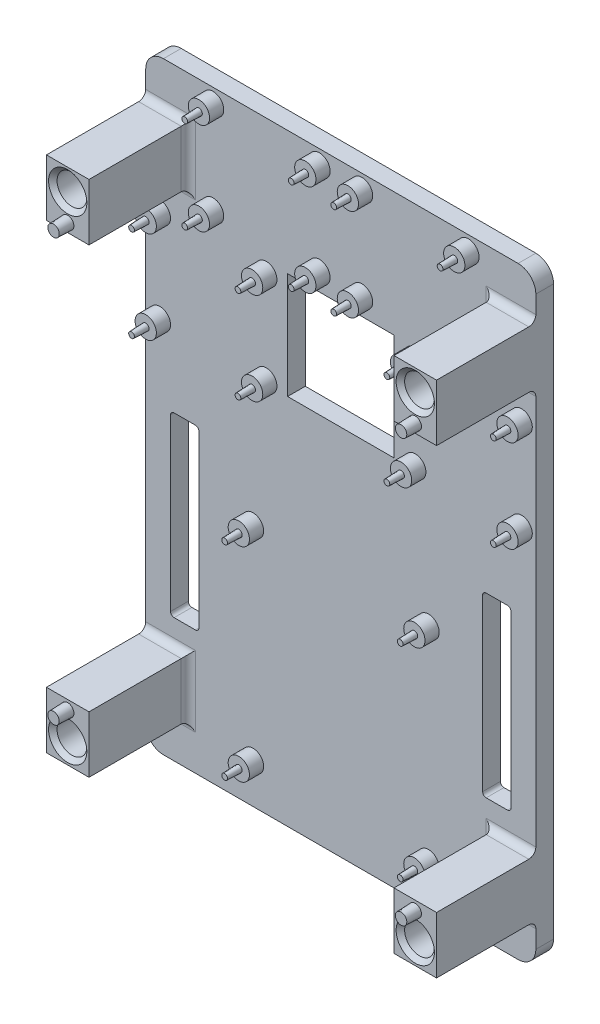
SolidWorks part; units mm, degrees
ref_plane "Ebene vorne" through (0, 0, 0) normal (0, 0, 1) x (1, 0, 0)
ref_plane "Ebene oben" through (0, 0, 0) normal (0, 1, 0) x (1, 0, 0)
ref_plane "Ebene rechts" through (0, 0, 0) normal (1, 0, 0) x (0, 0, -1)
sketch "Skizze1" plane through (0, 0, 0) normal (0, 0, 1) x (1, 0, 0)
  line L1 (-55, -85) -> (55, -85)
  line L2 (-55, -85) -> (-55, 85)
  line L3 (-55, 85) -> (55, 85)
  line L4 (55, -85) -> (55, 85)
  line L5 (-55, -85) -> (55, 85) construction
  line L6 (-55, 85) -> (55, -85) construction
  point P0 (0, 0)
  dimension "D1" = 110
  dimension "D2" = 170
extrude "Aufsatz-Linear austragen1" add sketch "Skizze1" along normal blind 5
fillet "Verrundung1" radius 5 4 edges at (-55, -85, 2.5) (55, -85, 2.5) (55, 85, 2.5) (-55, 85, 2.5)
sketch "Skizze7" plane through (0, 0, 5) normal (0, 0, 1) x (1, 0, 0)
  line L0 (-55, 80) -> (-55, -80) construction
  line L1 (-55, 73) -> (-43, 73)
  line L2 (-55, 73) -> (-55, 57)
  line L3 (-55, 57) -> (-43, 57)
  line L4 (-43, 73) -> (-43, 57)
  line L5 (50, 85) -> (-50, 85) construction
  line L18 (0, 85) -> (0, -85) construction
  line L19 (-50, -85) -> (50, -85) construction
  line L20 (-55, 0) -> (55, 0) construction
  line L21 (55, -80) -> (55, 80) construction
  line L22 (43, 73) -> (43, 57)
  line L23 (55, 57) -> (43, 57)
  line L24 (55, 73) -> (55, 57)
  line L25 (55, 73) -> (43, 73)
  line L26 (55, -73) -> (43, -73)
  line L27 (55, -73) -> (55, -57)
  line L28 (55, -57) -> (43, -57)
  line L29 (43, -73) -> (43, -57)
  line L30 (-43, -73) -> (-43, -57)
  line L31 (-55, -57) -> (-43, -57)
  line L32 (-55, -73) -> (-55, -57)
  line L33 (-55, -73) -> (-43, -73)
  dimension "D1" = 12
  dimension "D2" = 16
  dimension "D3" = 12
extrude "Aufsatz-Linear austragen3" add sketch "Skizze7" along normal blind 28
fillet "Verrundung2" radius 2 12 edges at (-49, 73, 5) (-49, 57, 5) (-43, 65, 5) (-49, -57, 5) (-43, -65, 5) (-49, -73, 5) (49, -73, 5) (43, -65, 5) (49, -57, 5) (49, 57, 5) (43, 65, 5) (49, 73, 5)
sketch "Skizze8" plane through (0, 0, 33) normal (0, 0, 1) x (1, 0, 0)
  line L0 (-43, 73) -> (-55, 73) construction
  line L1 (-55, 73) -> (-55, 57) construction
  line L5 (-55, 31.954) -> (-55, -16.1316) construction
  line L8 (-55, 55) -> (-55, -55) construction
  circle A1 centre (-49, 67) radius 4.2
  point P12 (0, 0)
  dimension "D1" = 8.4
  dimension "D2" = 6
  dimension "D3" = 6
extrude "Schnitt-Linear austragen3" cut sketch "Skizze8" against normal through all
pattern_linear "Lineares Muster1" count 2 spacing 134 along (0, -1, 0) count 2 spacing 98 along (1, 0, 0) of "Schnitt-Linear austragen3"
sketch "Skizze9" plane through (0, 0, 5) normal (0, 0, 1) x (1, 0, 0)
  line L0 (0, 85) -> (0, -85) construction
  line L1 (-28, -77) -> (28, -77) construction
  line L2 (-28, -77) -> (-28, 12) construction
  line L3 (-28, 12) -> (28, 12) construction
  line L4 (28, -77) -> (28, 12) construction
  line L5 (-28, -77) -> (28, 12) construction
  line L6 (-28, 12) -> (28, -77) construction
  line L11 (50, 85) -> (-50, 85) construction
  line L12 (-50, -85) -> (50, -85) construction
  line L13 (-55, 55) -> (-55, -55) construction
  line L14 (-51, 21) -> (-21, 21) construction
  line L15 (-51, 21) -> (-51, 47) construction
  line L16 (-51, 47) -> (-21, 47) construction
  line L17 (-21, 21) -> (-21, 47) construction
  line L18 (-51, 21) -> (-21, 47) construction
  line L19 (-51, 47) -> (-21, 21) construction
  line L21 (-36, 55) -> (-6, 55) construction
  line L22 (-36, 55) -> (-36, 81) construction
  line L23 (-36, 81) -> (-6, 81) construction
  line L24 (-6, 55) -> (-6, 81) construction
  line L25 (-36, 55) -> (-6, 81) construction
  line L26 (-36, 81) -> (-6, 55) construction
  line L27 (51, 47) -> (21, 47) construction
  line L28 (21, 21) -> (21, 47) construction
  line L29 (51, 21) -> (21, 21) construction
  line L30 (51, 21) -> (51, 47) construction
  line L31 (36, 81) -> (6, 81) construction
  line L32 (6, 55) -> (6, 81) construction
  line L33 (36, 55) -> (6, 55) construction
  line L34 (36, 55) -> (36, 81) construction
  circle A0 centre (24.75, -73.75) radius 3
  circle A1 centre (24.75, -16.25) radius 3
  circle A2 centre (-24.75, -16.25) radius 3
  circle A3 centre (-24.75, -73.75) radius 3
  circle A4 centre (-36, 81) radius 3
  circle A5 centre (-6, 81) radius 3
  circle A6 centre (-36, 55) radius 3
  circle A7 centre (-6, 55) radius 3
  circle A8 centre (6, 81) radius 3
  circle A9 centre (36, 81) radius 3
  circle A10 centre (36, 55) radius 3
  circle A11 centre (6, 55) radius 3
  circle A12 centre (21, 47) radius 3
  circle A13 centre (51, 47) radius 3
  circle A14 centre (51, 21) radius 3
  circle A15 centre (21, 21) radius 3
  circle A16 centre (-21, 47) radius 3
  circle A17 centre (-51, 47) radius 3
  circle A18 centre (-51, 21) radius 3
  circle A19 centre (-21, 21) radius 3
  point P0 (0, 0)
  point P5 (0, -32.5)
  point P21 (-36, 34)
  point P28 (-21, 68)
  dimension "D3" = 3.25
  dimension "D4" = 6
  dimension "D5" = 57.5
  dimension "D17" = 6
  dimension "D1" = 56
  dimension "D2" = 89
  dimension "D6" = 3.25
  dimension "D7" = 8
  dimension "D8" = 28
  dimension "D9" = 26
  dimension "D10" = 30
  dimension "D11" = 4
  dimension "D12" = 38
  dimension "D13" = 26
  dimension "D14" = 30
  dimension "D15" = 4
  dimension "D16" = 19
extrude "Aufsatz-Linear austragen4" add sketch "Skizze9" along normal blind 4
sketch "Skizze10" plane through (0, 0, 9) normal (0, 0, 1) x (1, 0, 0)
  line L0 (0, -85) -> (0, 85) construction
  line L1 (-50, -85) -> (50, -85) construction
  line L2 (50, 85) -> (-50, 85) construction
  circle A0 centre (24.75, -73.75) radius 0.95
  circle A1 centre (24.75, -16.25) radius 0.95
  circle A2 centre (-24.75, -16.25) radius 0.95
  circle A3 centre (-24.75, -73.75) radius 0.95
  circle A4 centre (-51, 47) radius 0.95
  circle A5 centre (-51, 21) radius 0.95
  circle A6 centre (-21, 21) radius 0.95
  circle A7 centre (-21, 47) radius 0.95
  circle A8 centre (-36, 55) radius 0.95
  circle A9 centre (-6, 55) radius 0.95
  circle A10 centre (6, 55) radius 0.95
  circle A11 centre (-36, 81) radius 0.95
  circle A12 centre (-6, 81) radius 0.95
  circle A13 centre (6, 81) radius 0.95
  circle A14 centre (36, 81) radius 0.95
  circle A15 centre (36, 55) radius 0.95
  circle A16 centre (21, 47) radius 0.95
  circle A17 centre (51, 47) radius 0.95
  circle A18 centre (21, 21) radius 0.95
  circle A19 centre (51, 21) radius 0.95
  dimension "D1" = 1.9
extrude "Aufsatz-Linear austragen5" add sketch "Skizze10" along normal blind 4 draft 2
chamfer "Fase1" distance 1.2 angle 45 4 edges at (-44.8, 67, 33) (-44.8, -67, 33) (53.2, -67, 33) (53.2, 67, 33)
sketch "Skizze11" plane through (0, 0, 5) normal (0, 0, 1) x (1, 0, 0)
  line L0 (0, 85) -> (0, -85) construction
  line L1 (-15, 20) -> (15, 20)
  line L2 (-15, 20) -> (-15, 50)
  line L3 (-15, 50) -> (15, 50)
  line L4 (15, 20) -> (15, 50)
  line L5 (-15, 20) -> (15, 50) construction
  line L6 (-15, 50) -> (15, 20) construction
  line L7 (50, 85) -> (-50, 85) construction
  line L8 (-50, -85) -> (50, -85) construction
  point P0 (0, 35)
  dimension "D1" = 30
  dimension "D2" = 30
  dimension "D3" = 35
extrude "Schnitt-Linear austragen4" cut sketch "Skizze11" against normal through all
sketch "Skizze12" plane through (0, 0, 33) normal (0, 0, 1) x (1, 0, 0)
  line L0 (-49, 73) -> (-49, 57) construction
  line L1 (-43, 73) -> (-55, 73) construction
  line L2 (-55, 57) -> (-43, 57) construction
  line L3 (-43, 67) -> (-55, 67) construction
  line L4 (-43, 57) -> (-43, 73) construction
  line L5 (-55, 73) -> (-55, 57) construction
  line L6 (0, 85) -> (0, -85) construction
  line L7 (50, 85) -> (-50, 85) construction
  line L8 (-50, -85) -> (50, -85) construction
  line L9 (-55, 0) -> (55, 0) construction
  line L10 (-55, 55) -> (-55, -55) construction
  line L11 (55, -55) -> (55, 55) construction
  circle A0 centre (-49, 59.5) radius 1.75
  circle A1 centre (49, 59.5) radius 1.75
  circle A2 centre (-49, -59.5) radius 1.75
  circle A3 centre (49, -59.5) radius 1.75
  dimension "D1" = 3.5
  dimension "D2" = 7.5
extrude "Aufsatz-Linear austragen6" add sketch "Skizze12" along normal blind 4 draft 2
sketch "Skizze13" plane through (0, 0, 0) normal (0, 0, -1) x (-1, 0, 0)
  line L0 (49, 71.2) -> (49, 62.8) construction
  line L1 (44.8, 67) -> (53.2, 67) construction
  line L2 (0, 85) -> (0, -85) construction
  line L3 (-50, 85) -> (50, 85) construction
  line L4 (50, -85) -> (-50, -85) construction
  line L5 (-55, 0) -> (55, 0) construction
  line L6 (-55, -80) -> (-55, 80) construction
  line L7 (55, 80) -> (55, -80) construction
  circle A0 centre (49, 67) radius 4.2 construction
  circle A1 centre (49, 59.5) radius 2
  circle A2 centre (-49, 59.5) radius 2
  circle A3 centre (-49, -59.5) radius 2
  circle A4 centre (49, -59.5) radius 2
  dimension "D1" = 4
  dimension "D2" = 7.5
extrude "Schnitt-Linear austragen5" cut sketch "Skizze13" against normal blind 4.5
sketch "Skizze15" plane through (0, 0, 5) normal (0, 0, 1) x (1, 0, 0)
  line L0 (55, -55) -> (55, 55) construction
  line L1 (48, -50) -> (40, -50)
  line L2 (48, -50) -> (48, 0)
  line L3 (48, 0) -> (40, 0)
  line L4 (40, -50) -> (40, 0)
  line L5 (-50, -85) -> (50, -85) construction
  line L6 (0, -85) -> (0, 85) construction
  line L7 (50, 85) -> (-50, 85) construction
  line L8 (-48, 0) -> (-40, 0)
  line L9 (-40, -50) -> (-40, 0)
  line L10 (-48, -50) -> (-40, -50)
  line L11 (-48, -50) -> (-48, 0)
  dimension "D1" = 50
  dimension "D2" = 8
  dimension "D3" = 7
  dimension "D4" = 35
extrude "Schnitt-Linear austragen6" cut sketch "Skizze15" against normal through all
fillet "Verrundung3" radius 1 8 edges at (48, 0, 2.5) (40, 0, 2.5) (48, -50, 2.5) (40, -50, 2.5) (-40, -50, 2.5) (-48, -50, 2.5) (-40, 0, 2.5) (-48, 0, 2.5)
